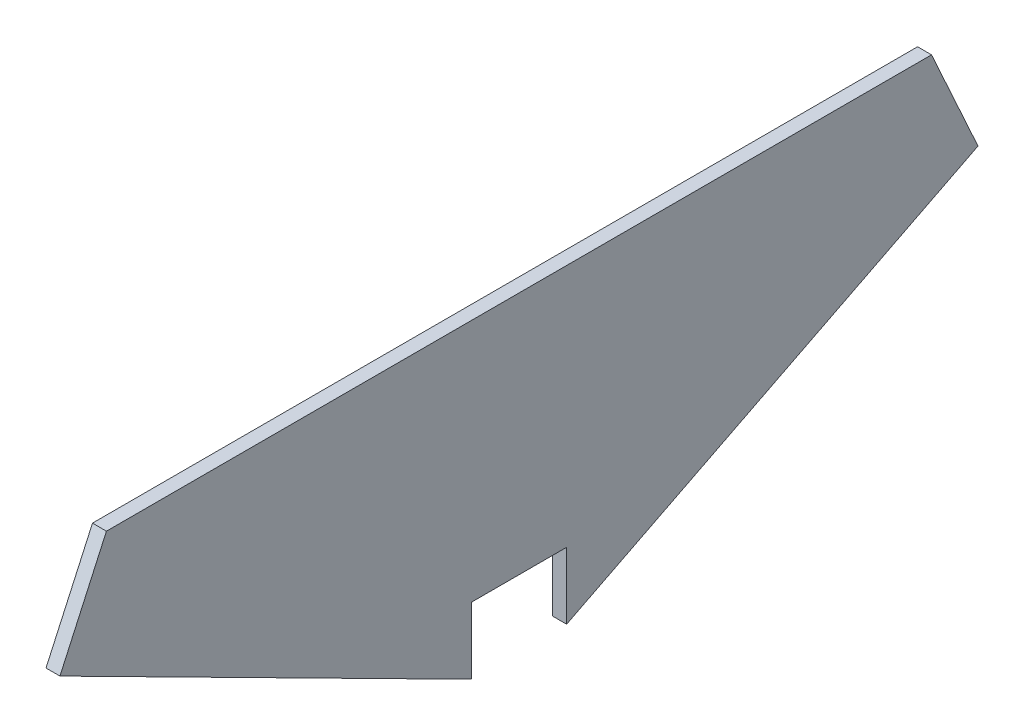
SolidWorks part; units mm, degrees
material "ASTM A36 Steel"
ref_plane "Front Plane" through (0, 0, 0) normal (0, 0, 1) x (1, 0, 0)
ref_plane "Top Plane" through (0, 0, 0) normal (0, 1, 0) x (1, 0, 0)
ref_plane "Right Plane" through (0, 0, 0) normal (1, 0, 0) x (0, 0, -1)
sketch "Sketch1" plane through (0, 0, 0) normal (1, 0, 0) x (0, 0, -1)
  line L0 (173.4466, 74.1105) -> (-181.5534, 74.1105)
  line L1 (-181.5534, 74.1105) -> (-201.5534, 30.1105)
  line L2 (173.4466, 74.1105) -> (193.4466, 30.1105)
  line L3 (-24.5534, -59.566) -> (-24.5534, -30.8895)
  line L4 (-24.5534, -30.8895) -> (16.4466, -30.8895)
  line L5 (16.4466, -59.566) -> (16.4466, -30.8895)
  line L6 (193.4466, 30.1105) -> (16.4466, -59.566)
  line L7 (-201.5534, 30.1105) -> (-24.5534, -59.566)
extrude "Boss-Extrude1" add sketch "Sketch1" along normal blind 6
